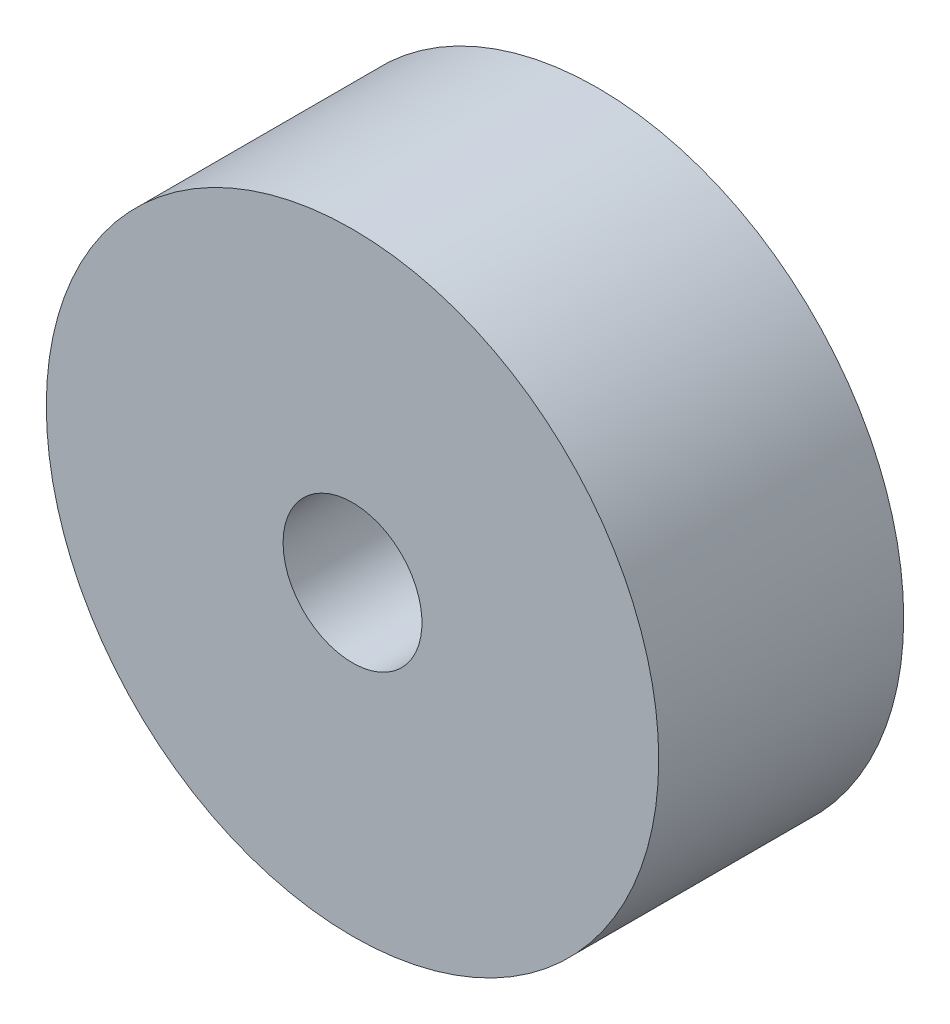
SolidWorks part; units mm, degrees
ref_plane "Front Plane" through (0, 0, 0) normal (0, 0, 1) x (1, 0, 0)
ref_plane "Top Plane" through (0, 0, 0) normal (0, 1, 0) x (1, 0, 0)
ref_plane "Right Plane" through (0, 0, 0) normal (1, 0, 0) x (0, 0, -1)
ref_plane "Plane1" through (0, 0, 0) normal (0, -1, 0) x (1, 0, 0)
sketch "Sketch1" plane through (0, 0, 0) normal (0, -1, 0) x (1, 0, 0)
  line L0 (0.7937, 2.8) -> (0.7937, 0)
  line L1 (0.7937, 0) -> (3.5, 0)
  line L2 (3.5, 0) -> (3.5, 2.8)
  line L3 (3.5, 2.8) -> (0.7937, 2.8)
  line L4 (0, 2.8) -> (0, 0) construction
revolve "Revolve1" add sketch "Sketch1" angle 360 about L4
